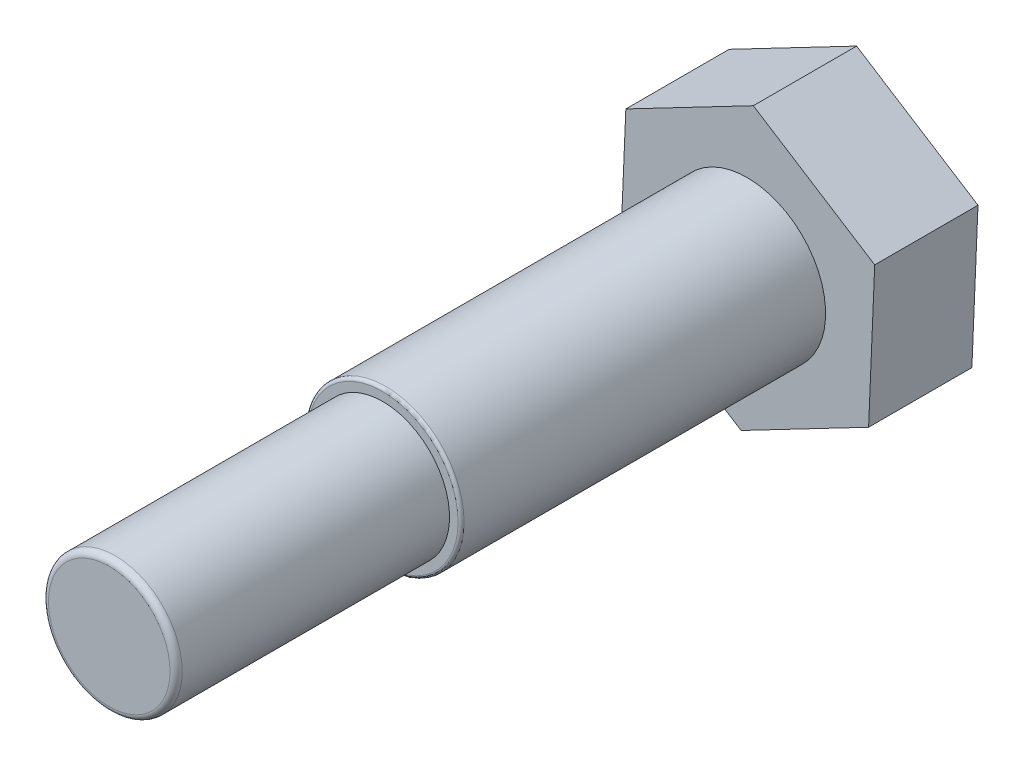
SolidWorks part; units mm, degrees
ref_plane "前视" through (0, 0, 0) normal (0, 0, 1) x (1, 0, 0)
ref_plane "上视" through (0, 0, 0) normal (0, 1, 0) x (1, 0, 0)
ref_plane "右视" through (0, 0, 0) normal (1, 0, 0) x (0, 0, -1)
sketch "草图1" plane through (0, 0, 0) normal (0, 0, 1) x (1, 0, 0)
  line L1 (20.9842, 10.9543) -> (1.0054, 23.65)
  line L2 (1.0054, 23.65) -> (-19.9788, 12.6957)
  line L3 (-19.9788, 12.6957) -> (-20.9842, -10.9543)
  line L4 (-20.9842, -10.9543) -> (-1.0054, -23.65)
  line L5 (-1.0054, -23.65) -> (19.9788, -12.6957)
  line L6 (19.9788, -12.6957) -> (20.9842, 10.9543)
  circle A0 centre (0, 0) radius 20.5 construction
  dimension "D1" = 47.3
  dimension "D2" = 41
extrude "基体-拉伸" add sketch "草图1" along normal blind 17
sketch "草图2" plane through (0, 0, 17) normal (0, 0, 1) x (1, 0, 0)
  circle A0 centre (0, 0) radius 12.9
  dimension "D1" = 25.8
extrude "凸台-拉伸1" add sketch "草图2" along normal blind 60
sketch "草图3" plane through (0, 0, 77) normal (0, 0, 1) x (1, 0, 0)
  circle A0 centre (0, 0) radius 11
  dimension "D1" = 22
extrude "凸台-拉伸2" add sketch "草图3" along normal blind 45
fillet "圆角2" radius 1 1 edges at (11, 0, 122)
fillet "圆角4" radius 0.5 1 edges at (12.9, 0, 77)
